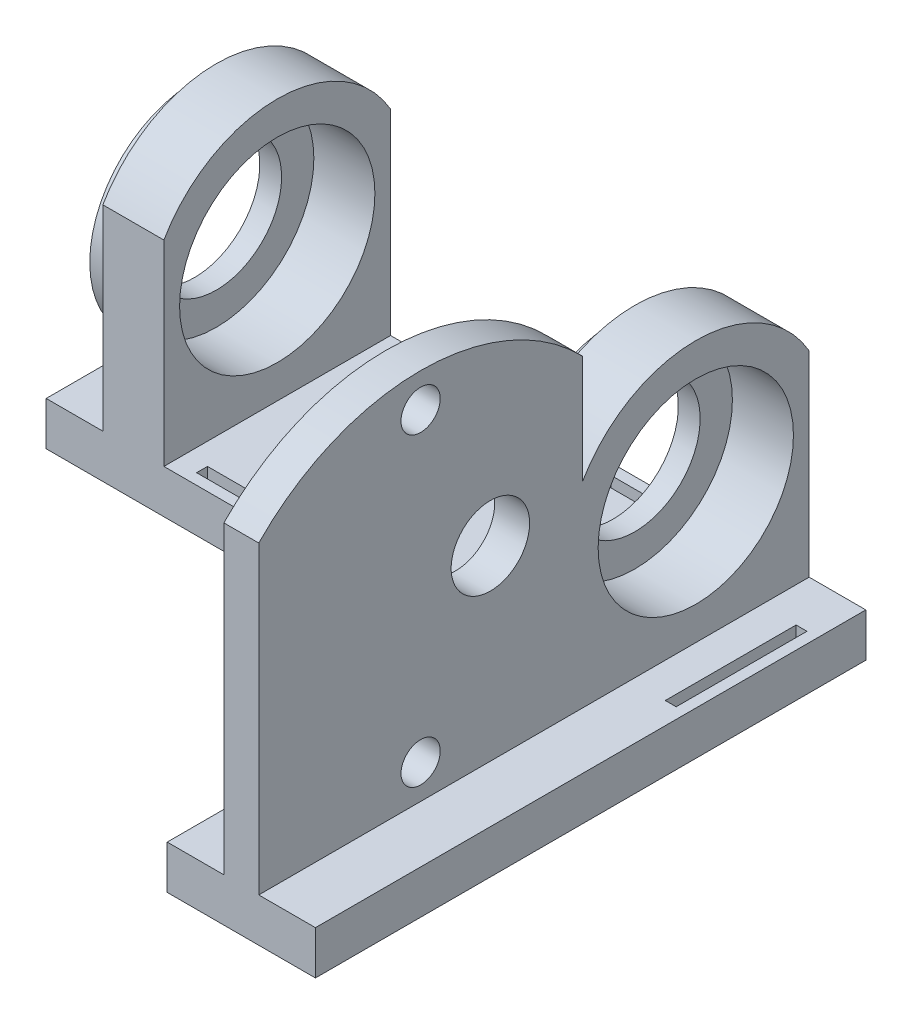
SolidWorks part; units mm, degrees
ref_plane "Front Plane" through (0, 0, 0) normal (0, 0, 1) x (1, 0, 0)
ref_plane "Top Plane" through (0, 0, 0) normal (0, 1, 0) x (1, 0, 0)
ref_plane "Right Plane" through (0, 0, 0) normal (1, 0, 0) x (0, 0, -1)
sketch "Sketch1" plane through (0, 0, 0) normal (0, 1, 0) x (1, 0, 0)
  line L0 (0, 0) -> (20, 0)
  line L1 (0, 0) -> (0, 26)
  line L2 (0, 26) -> (20, 26)
  line L3 (20, 26) -> (20, 0)
  line L4 (0, 26) -> (1.6662, 26)
  line L5 (2.5, 20.5) -> (2.5, 5.5)
  line L6 (20, 26) -> (16.6758, 26)
  line L8 (0, 26) -> (0.8331, 26)
  line L9 (1.25, 20.5) -> (1.25, 5.5)
  line L13 (0, 13) -> (20, 13) construction
  line L16 (2.5, 20.5) -> (1.25, 20.5)
  line L18 (2.5, 5.5) -> (1.25, 5.5)
  line L19 (10, 26) -> (10, 0) construction
  line L28 (14.1758, 26) -> (10, 26)
  dimension "D1" = 20
  dimension "D2" = 26
  dimension "D3" = 15
  dimension "D4" = 1.25
  dimension "D5" = 1.25
  dimension "D6" = 5.5
extrude "Boss-Extrude5" add sketch "Sketch1" along normal blind 5
sketch "Sketch3" plane through (0, 5, 0) normal (0, 1, 0) x (1, 0, 0)
  line L0 (2.5, 20.5) -> (2.5, 5.5) construction
  line L5 (6.5, 0) -> (13.5, 0)
  line L6 (6.5, 0) -> (6.5, 26)
  line L7 (6.5, 26) -> (13.5, 26)
  line L8 (13.5, 0) -> (13.5, 26)
  line L9 (6.5, 0) -> (13.5, 26) construction
  line L10 (6.5, 26) -> (13.5, 0) construction
  line L11 (0, 26) -> (20, 26) construction
  point P0 (10, 13)
  dimension "D1" = 7.5
  dimension "D2" = 7
  dimension "D3" = 26
  dimension "D4" = 13
extrude "Boss-Extrude6" add sketch "Sketch3" along normal blind 40
sketch "Sketch5" plane through (13.5, 0, 0) normal (1, 0, 0) x (0, 0, -1)
  line L2 (13, 45) -> (13, 5) construction
  line L3 (0, 45) -> (26, 45) construction
  line L4 (0, 5) -> (26, 5) construction
  line L5 (26, 5) -> (0, 5) construction
  line L6 (0, 27.4833) -> (0, 45)
  line L7 (0, 45) -> (26, 45)
  line L10 (26, 45) -> (26, 27.4833)
  line L16 (26, 45) -> (26, 5) construction
  circle A0 centre (13, 20) radius 11.2
  arc A3 (26, 27.4833) -> (0, 27.4833) centre (13, 20) ccw
  dimension "D1" = 15
  dimension "D2" = 22.4
  dimension "D3" = 30
extrude "Cut-Extrude1" cut sketch "Sketch5" against normal up to next
sketch "Sketch6" plane through (20, 0, 0) normal (1, 0, 0) x (0, 0, -1)
  line L1 (0, 0) -> (26, 0)
  line L2 (0, 0) -> (0, 5)
  line L3 (0, 5) -> (26, 5)
  line L4 (26, 0) -> (26, 5)
extrude "Boss-Extrude8" add sketch "Sketch6" along normal blind 14
mirror "Mirror5" about plane through (34, 0, 0) normal (-1, 0, 0) of "Cut-Extrude1", "Boss-Extrude8", "Boss-Extrude6", "Boss-Extrude5"
sketch "Sketch7" plane through (0, 5, 0) normal (0, 1, 0) x (1, 0, 0)
  line L0 (34, 26) -> (34, 0) construction
  line L5 (13.5, 0) -> (13.5, 26) construction
  line L6 (16, 2.5) -> (28, 2.5)
  line L7 (16, 2.5) -> (16, 1.25)
  line L8 (13.5, 0) -> (54.5, 0) construction
  line L9 (13.5, 0) -> (13.5, 26) construction
  line L10 (13.5, 13) -> (54.5, 13) construction
  line L11 (16, 1.25) -> (28, 1.25)
  line L12 (28, 2.5) -> (28, 1.25)
  line L13 (54.5, 0) -> (54.5, 26) construction
  line L14 (13.5, 26) -> (54.5, 26) construction
  line L15 (40, 2.5) -> (40, 1.25)
  line L16 (52, 1.25) -> (40, 1.25)
  line L17 (52, 2.5) -> (52, 1.25)
  line L18 (52, 2.5) -> (40, 2.5)
  line L19 (52, 23.5) -> (40, 23.5)
  line L20 (52, 23.5) -> (52, 24.75)
  line L21 (52, 24.75) -> (40, 24.75)
  line L22 (40, 23.5) -> (40, 24.75)
  line L23 (28, 23.5) -> (28, 24.75)
  line L24 (16, 24.75) -> (28, 24.75)
  line L25 (16, 23.5) -> (16, 24.75)
  line L26 (16, 23.5) -> (28, 23.5)
  dimension "D1" = 1.25
  dimension "D2" = 12
  dimension "D3" = 1.25
  dimension "D4" = 2.5
sketch "Sketch8" plane through (6.5, 0, 0) normal (-1, 0, 0) x (0, 0, 1)
  circle A0 centre (-13, 20) radius 11.2 construction
  circle A3 centre (-13, 20) radius 12
  circle A4 centre (-13, 20) radius 7.5
  point P4 (-13, 20)
  dimension "D1" = 15
  dimension "D2" = 24
extrude "Boss-Extrude9" add sketch "Sketch8" along normal blind 2.5
sketch "Sketch9" plane through (54.5, 0, 0) normal (-1, 0, 0) x (0, 0, 1)
  circle A0 centre (-13, 20) radius 7.5 construction
  circle A1 centre (-13, 20) radius 12
  circle A2 centre (-13, 20) radius 12
  circle A3 centre (-13, 20) radius 7.5
  dimension "D1" = 0
extrude "Boss-Extrude10" add sketch "Sketch9" along normal blind 2.5
extrude "Cut-Extrude2" cut sketch "Sketch7" against normal blind 10
sketch "Sketch10" plane through (0, 0, 0) normal (0, 0, 1) x (1, 0, 0)
  line L11 (51, 0) -> (68, 0)
  line L12 (51, 5) -> (51, 0)
  line L13 (57.5, 5) -> (51, 5)
  line L14 (57.5, 47.8) -> (57.5, 5)
  line L15 (61.5, 47.8) -> (57.5, 47.8)
  line L16 (61.5, 5) -> (61.5, 47.8)
  line L17 (68, 5) -> (61.5, 5)
  line L18 (68, 0) -> (68, 5)
  dimension "D3" = 4
  dimension "D4" = 42.8
extrude "Boss-Extrude11" add sketch "Sketch10" along normal blind 37.12
sketch "Sketch13" plane through (0, 5, 0) normal (0, 1, 0) x (1, 0, 0)
  line L0 (28, 2.5) -> (40, 2.5)
  line L1 (34, 2.5) -> (34, 26)
  line L2 (13.5, 26) -> (54.5, 26) construction
ref_plane "Plane2" through (34, 0, 0) normal (1, 0, 0) x (0, 0, -1)
sketch "Sketch14" plane through (61.5, 0, 0) normal (1, 0, 0) x (0, 0, -1)
  line L8 (-15.0569, 39.9524) -> (-15.0569, 43.897) construction
  line L9 (-22.0569, 39.9524) -> (-22.0569, 43.897) construction
  line L10 (-22.0569, 12.8415) -> (-22.0569, 8.897) construction
  line L11 (-15.0569, 12.8415) -> (-15.0569, 8.897) construction
  line L15 (-37.12, 5) -> (-37.12, 47.8) construction
  line L16 (-37.12, 39.9524) -> (-37.12, 51.8324)
  line L17 (-37.12, 51.8324) -> (0, 51.8324)
  line L18 (0, 51.8324) -> (0, 39.9524)
  arc A10 (-15.0569, 39.9524) -> (-15.0569, 12.8415) centre (-18.5569, 26.397) cw construction
  arc A11 (-22.0569, 43.897) -> (-15.0569, 43.897) centre (-18.5569, 43.897) cw construction
  arc A12 (-22.0569, 8.897) -> (-15.0569, 8.897) centre (-18.5569, 8.897) ccw construction
  arc A13 (-22.0569, 12.8415) -> (-22.0569, 39.9524) centre (-18.5569, 26.397) cw construction
  circle A14 centre (13, 20) radius 24.41 construction
  circle A16 centre (-18.5569, 43.897) radius 2.25
  circle A17 centre (-10.5569, 26.397) radius 4.5
  circle A18 centre (-18.5569, 43.897) radius 2.25
  circle A19 centre (-18.5569, 8.897) radius 2.25
  arc A20 (-37.12, 39.9524) -> (0, 39.9524) centre (-18.56, 21.9284) cw
  point P0 (-10.5569, 26.397)
  point P50 (-10.5569, 26.397)
  line M10 (0, 27.4833) -> (0, 47.8)
  line M11 (0, 47.8) -> (-37.12, 47.8)
  line M12 (-37.12, 47.8) -> (-37.12, 5)
  dimension "D1" = 48.82
extrude "Cut-Extrude4" cut sketch "Sketch14" against normal blind 10 contours L18 L17 L16 M11 | A20 M11 M10 | A20 M12 M11 | A16 | A17 | A19
